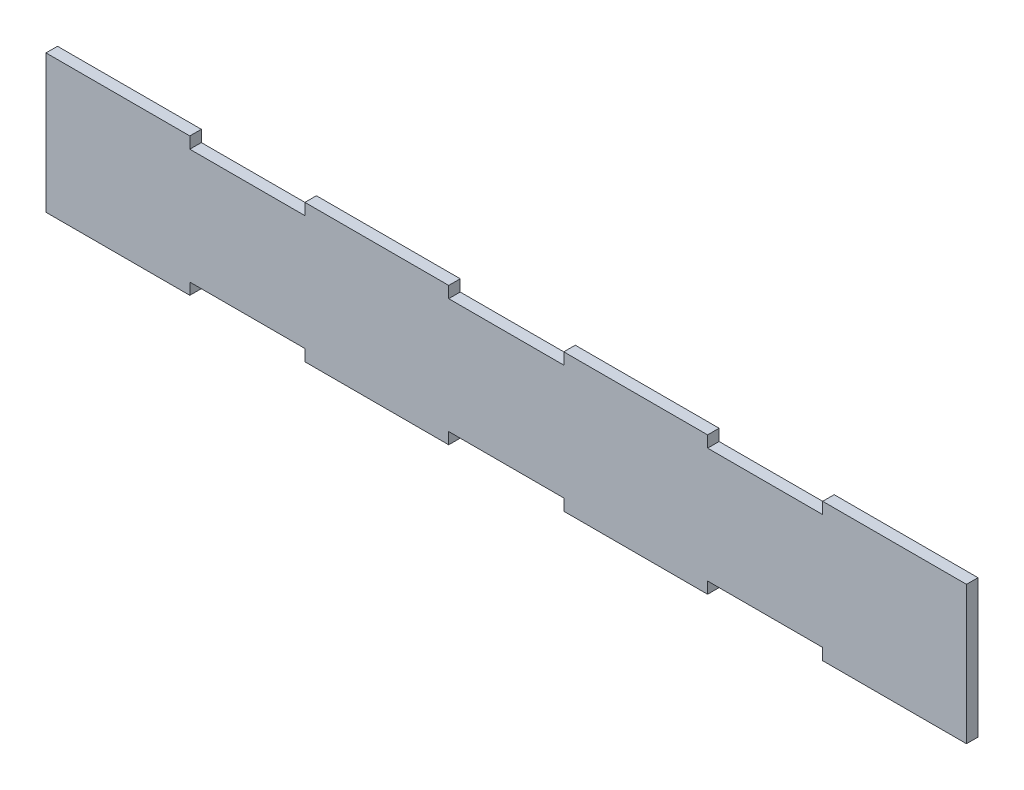
SolidWorks part; units mm, degrees
ref_plane "Спереди" through (0, 0, 0) normal (0, 0, 1) x (1, 0, 0)
ref_plane "Сверху" through (0, 0, 0) normal (0, 1, 0) x (1, 0, 0)
ref_plane "Справа" through (0, 0, 0) normal (1, 0, 0) x (0, 0, -1)
sketch "Эскиз1" plane through (0, 0, 0) normal (0, 0, 1) x (1, 0, 0)
  line L0 (135, 0) -> (160, 0)
  line L1 (0, 0) -> (25, 0)
  line L2 (0, 0) -> (0, 24)
  line L3 (21.9832, 24) -> (25, 24)
  line L4 (160, 0) -> (160, 24)
  line L5 (0, 24) -> (25, 24)
  line L6 (0, 24) -> (0, 22)
  line L8 (25, 24) -> (25, 22)
  line L9 (45, 24) -> (70, 24)
  line L10 (45, 24) -> (45, 22)
  line L12 (70, 24) -> (70, 22)
  line L13 (90, 24) -> (115, 24)
  line L14 (90, 24) -> (90, 22)
  line L16 (115, 24) -> (115, 22)
  line L17 (0, 0) -> (25, 0)
  line L18 (0, 0) -> (0, 2)
  line L20 (25, 0) -> (25, 2)
  line L21 (45, 0) -> (70, 0)
  line L22 (45, 0) -> (45, 2)
  line L24 (70, 0) -> (70, 2)
  line L26 (90, 0) -> (90, 2)
  line L28 (115, 0) -> (115, 2)
  line L29 (160, 24) -> (135, 24)
  line L30 (160, 24) -> (160, 22)
  line L32 (135, 24) -> (135, 22)
  line L33 (160, 0) -> (135, 0)
  line L34 (160, 0) -> (160, 2)
  line L36 (135, 0) -> (135, 2)
  line L37 (115, 0) -> (90, 0)
  line L38 (25, 22) -> (45, 22)
  line L39 (70, 22) -> (90, 22)
  line L40 (115, 22) -> (135, 22)
  line L41 (25, 2) -> (45, 2)
  line L42 (70, 2) -> (90, 2)
  line L43 (115, 2) -> (135, 2)
  line L44 (90, 24) -> (160, 24)
  line L45 (25.3892, 22) -> (45, 22)
  line L46 (45, 24) -> (70, 24)
  line L47 (45, 0) -> (70, 0)
  dimension "D1" = 24
  dimension "D2" = 160
  dimension "D3" = 2
  dimension "D4" = 2
  dimension "D5" = 2
  dimension "D6" = 2
  dimension "D7" = 2
  dimension "D8" = 2
  dimension "D9" = 25
  dimension "D10" = 25
  dimension "D11" = 25
  dimension "D12" = 25
  dimension "D13" = 25
  dimension "D14" = 25
  dimension "D15" = 20
  dimension "D16" = 20
  dimension "D17" = 20
  dimension "D18" = 20
  dimension "D19" = 20
  dimension "D20" = 20
  dimension "D21" = 2
  dimension "D22" = 2
extrude "Бобышка-Вытянуть1" add sketch "Эскиз1" along normal blind 2
